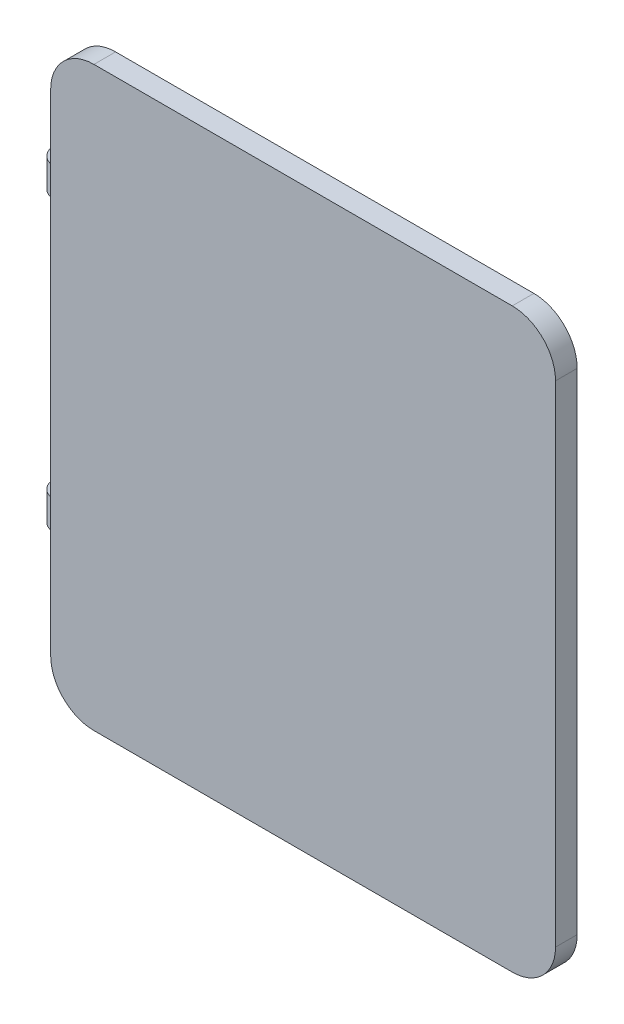
SolidWorks part; units mm, degrees
ref_plane "Front Plane" through (0, 0, 0) normal (0, 0, 1) x (1, 0, 0)
ref_plane "Top Plane" through (0, 0, 0) normal (0, 1, 0) x (1, 0, 0)
ref_plane "Right Plane" through (0, 0, 0) normal (1, 0, 0) x (0, 0, -1)
sketch "Sketch1" plane through (0, 0, 0) normal (0, 0, 1) x (1, 0, 0)
  line L0 (-238.7401, 0) -> (238.7401, 0) construction
  line L1 (0, 0) -> (0, 164.0151) construction
  line L2 (-175, -200) -> (-175, 200)
  line L3 (175, -200) -> (175, 200)
  line L4 (-175, 200) -> (175, 200)
  line L5 (-175, -200) -> (175, -200)
  point P4 (0, 0)
  point P10 (-175, 0)
  dimension "D1" = 400
  dimension "D2" = 350
extrude "Boss-Extrude1" add sketch "Sketch1" along normal blind 15
ref_plane "Plane1" through (0, 100, 0) normal (0, 1, 0) x (1, 0, 0)
ref_plane "Plane2" through (0, -100, 0) normal (0, 1, 0) x (1, 0, 0)
sketch "Sketch3" plane through (0, 100, 0) normal (0, 1, 0) x (1, 0, 0)
  line L0 (-175, 0) -> (-200, 0) construction
  line L1 (-200, 0) -> (-200, 12.5) construction
  line L2 (-200, 12.5) -> (-175, 12.5) construction
  line L3 (-175, 12.5) -> (-175, 0) construction
  line L4 (-187.5, 0) -> (-187.5, 12.5) construction
  line L5 (-187.5, 0) -> (-127.5, 0)
  line L6 (-182.5083, 23.9601) -> (-127.5, 0)
  line L7 (175, 0) -> (-175, 0) construction
  circle A0 centre (-187.5, 12.5) radius 10
  circle A1 centre (-187.5, 12.5) radius 12.5
  dimension "D3" = 20
  dimension "D4" = 25
  dimension "D1" = 25
  dimension "D2" = 12.5
  dimension "D5" = 60
extrude "Boss-Extrude2" add sketch "Sketch3" along normal blind 10 and the other way blind 10 contours A1 L5 L6 | A1 A0
sketch "Sketch4" plane through (0, -100, 0) normal (0, 1, 0) x (1, 0, 0)
  line L0 (-175, 0) -> (-200, 0) construction
  line L1 (-200, 0) -> (-200, 12.5) construction
  line L2 (-200, 12.5) -> (-175, 12.5) construction
  line L3 (-175, 12.5) -> (-175, 0) construction
  line L4 (-187.5, 0) -> (-187.5, 12.5) construction
  line L5 (-182.5083, 23.9601) -> (-127.5, 0)
  line L6 (175, 0) -> (-175, 0) construction
  line L7 (-127.5, 0) -> (-187.5, 0)
  circle A0 centre (-187.5, 12.5) radius 10
  circle A1 centre (-187.5, 12.5) radius 12.5
  dimension "D3" = 20
  dimension "D4" = 25
  dimension "D1" = 25
  dimension "D2" = 12.5
  dimension "D5" = 60
extrude "Boss-Extrude3" add sketch "Sketch4" along normal blind 10 and the other way blind 10 contours A1 A0 | A1 L7 L5
sketch "Sketch5" plane through (0, 0, 0) normal (0, 0, -1) x (-1, 0, 0)
  line L0 (-175, 170) -> (-175, -170)
  line L1 (-145, -200) -> (145, -200)
  line L2 (175, -170) -> (175, 170)
  line L3 (145, 200) -> (-145, 200)
  line L4 (-175, 170) -> (-175, 200)
  line L5 (-175, 200) -> (-145, 200)
  line L6 (145, 200) -> (175, 200)
  line L7 (175, 200) -> (175, 170)
  line L8 (145, -200) -> (175, -200)
  line L9 (175, -200) -> (175, -170)
  line L10 (-145, -200) -> (-175, -200)
  line L11 (-175, -200) -> (-175, -170)
  arc A0 (175, 170) -> (145, 200) centre (145, 170) ccw
  arc A1 (145, -200) -> (175, -170) centre (145, -170) ccw
  arc A2 (-175, -170) -> (-145, -200) centre (-145, -170) ccw
  arc A3 (-175, 170) -> (-145, 200) centre (-145, 170) cw
  point P10 (175, 200)
  point P13 (175, -200)
  point P16 (-175, -200)
  point P19 (-175, 200)
  line M14 (175, 110) -> (175, 200)
  line M15 (175, 200) -> (-175, 200)
  line M16 (-175, 200) -> (-175, -200)
  line M17 (-175, -200) -> (175, -200)
  line M18 (175, -200) -> (175, -110)
  dimension "D1" = 30
extrude "Cut-Extrude1" cut sketch "Sketch5" against normal blind 74 contours A3 M16 M15 | A2 M16 M17 | A1 M17 M18 | A0 M14 M15
sketch "Sketch6" plane through (0, 0, 0) normal (0, 0, -1) x (-1, 0, 0)
  line L0 (0, 0) -> (-175, 0) construction
  line L1 (-175, -170) -> (-175, 170) construction
  line L2 (-145, -40) -> (-145, 40) construction
  line L3 (145, -200) -> (-145, -200) construction
  circle A0 centre (-145, 40) radius 7.5
  circle A1 centre (-145, -40) radius 7.5
  point P8 (-145, 0)
  point P10 (0, 0)
  point P11 (0, 0)
  dimension "D1" = 15
  dimension "D2" = 80
  dimension "D3" = 30
extrude "Boss-Extrude4" add sketch "Sketch6" along normal blind 10
sketch "Sketch7" plane through (0, 0, -10) normal (0, 0, -1) x (-1, 0, 0)
  line L0 (0, 0) -> (-175, 0) construction
  line L1 (-175, -170) -> (-175, 170) construction
  line L2 (-145, 40) -> (-145, -40) construction
  line L3 (-145, 40) -> (-145, 64.248) construction
  line L4 (-145, -40) -> (-145, -73.6062) construction
  line L5 (-150, 50) -> (-140, 50)
  line L6 (-150, -50) -> (-140, -50)
  line L7 (-155, 45) -> (-155, -45)
  line L8 (-135, 45) -> (-135, -45)
  arc A0 (-140, -50) -> (-135, -45) centre (-140, -45) ccw
  arc A1 (-150, -50) -> (-155, -45) centre (-150, -45) cw
  arc A2 (-150, 50) -> (-155, 45) centre (-150, 45) ccw
  arc A3 (-140, 50) -> (-135, 45) centre (-140, 45) cw
  point P14 (-145, 50)
  point P18 (-135, -50)
  point P21 (-155, -50)
  point P24 (-155, 50)
  point P27 (-135, 50)
  dimension "D3" = 5
  dimension "D1" = 20
  dimension "D2" = 100
extrude "Boss-Extrude5" add sketch "Sketch7" along normal blind 5
